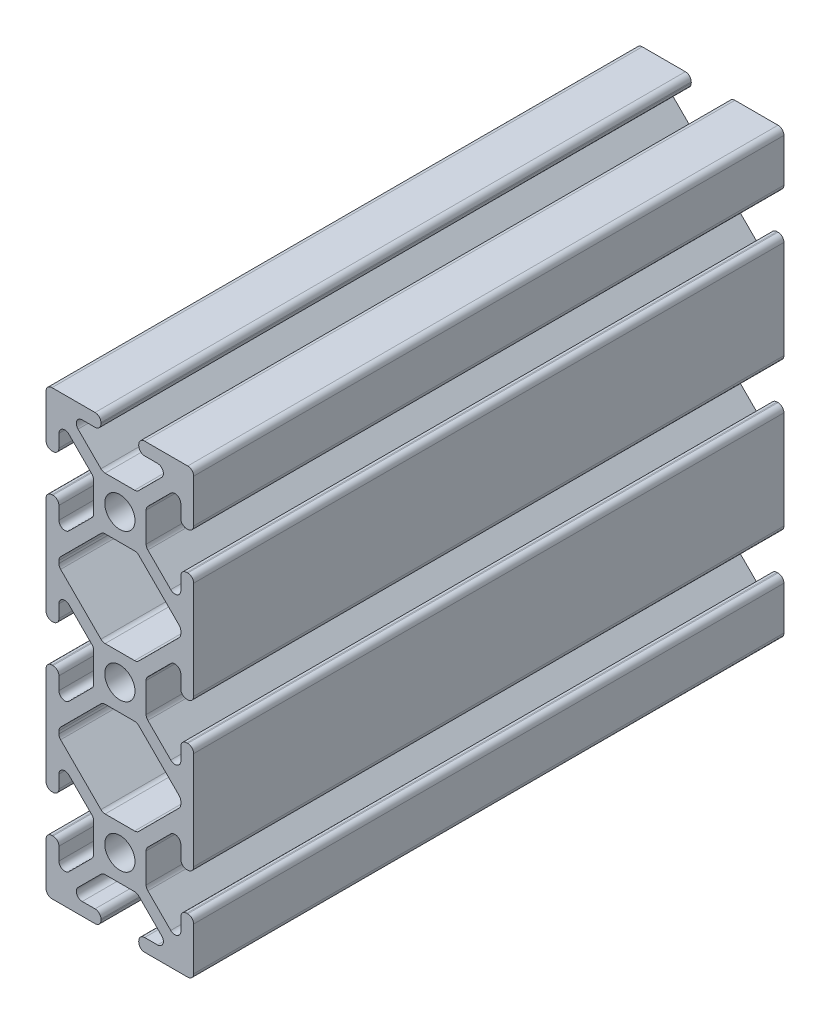
SolidWorks part; units mm, degrees
ref_plane "Front Plane" through (0, 0, 0) normal (0, 0, 1) x (1, 0, 0)
ref_plane "Top Plane" through (0, 0, 0) normal (0, 1, 0) x (1, 0, 0)
ref_plane "Right Plane" through (0, 0, 0) normal (1, 0, 0) x (0, 0, -1)
sketch "Sketch1" plane through (0, 0, 0) normal (0, 0, 1) x (1, 0, 0)
  line L0 (-12.7, 38.1) -> (-12.7, 12.7) construction
  line L1 (-12.7, -38.1) -> (12.7, -38.1) construction
  line L2 (-12.7, 12.7) -> (-12.7, -12.7) construction
  line L3 (-12.7, 38.1) -> (12.7, 38.1) construction
  line L4 (-12.7, -12.7) -> (-12.7, -38.1) construction
  line L5 (-12.7, -38.1) -> (12.7, 38.1) construction
  line L6 (-12.7, 38.1) -> (12.7, -38.1) construction
  line L7 (12.7, 38.1) -> (12.7, 12.7) construction
  line L8 (12.7, 12.7) -> (12.7, -12.7) construction
  line L9 (12.7, -12.7) -> (12.7, -38.1) construction
  line L10 (-12.7, 12.7) -> (12.7, 12.7) construction
  line L11 (-12.7, -12.7) -> (12.7, -12.7) construction
  line L12 (12.7, -12.7) -> (-12.7, -38.1) construction
  line L13 (12.7, -38.1) -> (-12.7, -12.7) construction
  line L14 (0, 38.1) -> (0, -38.1) construction
  line L15 (12.7, 12.7) -> (-12.7, 38.1) construction
  line L16 (12.7, 38.1) -> (-12.7, 12.7) construction
  line L17 (-12.7, 37.084) -> (-12.7, 29.6672)
  line L18 (-11.684, 28.6512) -> (-11.5062, 28.6512)
  line L19 (-10.4902, 29.6672) -> (-10.4902, 31.8748)
  line L20 (-8.7558, 32.5932) -> (-4.8188, 28.6562)
  line L21 (-4.5212, 27.9378) -> (-4.5212, 22.8622)
  line L22 (-4.8188, 22.1438) -> (-8.7558, 18.2068)
  line L23 (-10.4902, 18.9252) -> (-10.4902, 21.1328)
  line L24 (-11.5062, 22.1488) -> (-11.684, 22.1488)
  line L25 (-12.7, 21.1328) -> (-12.7, 4.2672)
  line L26 (-12.7, 0) -> (12.7, 0) construction
  line L27 (-12.7, -25.4) -> (12.7, -25.4) construction
  line L28 (-12.7, 25.4) -> (12.7, 25.4) construction
  line L29 (4.2672, 38.1) -> (11.684, 38.1)
  line L30 (3.2512, 36.9062) -> (3.2512, 37.084)
  line L31 (6.4748, 35.8902) -> (4.2672, 35.8902)
  line L32 (3.2562, 30.2188) -> (7.1932, 34.1558)
  line L33 (-2.5378, 29.9212) -> (2.5378, 29.9212)
  line L34 (-7.1932, 34.1558) -> (-3.2562, 30.2188)
  line L35 (-4.2672, 35.8902) -> (-6.4748, 35.8902)
  line L36 (-3.2512, 37.084) -> (-3.2512, 36.9062)
  line L37 (-11.684, 38.1) -> (-4.2672, 38.1)
  line L38 (4.5212, 2.5378) -> (4.5212, -2.5378)
  line L39 (11.5062, 22.1488) -> (11.684, 22.1488)
  line L40 (10.4902, 18.9252) -> (10.4902, 21.1328)
  line L41 (4.8188, 22.1438) -> (8.7558, 18.2068)
  line L42 (4.5212, 27.9378) -> (4.5212, 22.8622)
  line L43 (8.7558, 32.5932) -> (4.8188, 28.6562)
  line L44 (10.4902, 29.6672) -> (10.4902, 31.8748)
  line L45 (11.684, 28.6512) -> (11.5062, 28.6512)
  line L46 (12.7, 37.084) -> (12.7, 29.6672)
  line L47 (-10.4902, 12.4736) -> (-10.4902, 12.9264)
  line L48 (-10.1926, 13.6448) -> (-3.2562, 20.5812)
  line L49 (-2.5378, 20.8788) -> (2.5378, 20.8788)
  line L50 (10.4902, 12.4736) -> (10.4902, 12.9264)
  line L51 (10.1926, 13.6448) -> (3.2562, 20.5812)
  line L52 (10.1926, 11.7552) -> (3.2562, 4.8188)
  line L53 (-2.5378, 4.5212) -> (2.5378, 4.5212)
  line L54 (-10.1926, 11.7552) -> (-3.2562, 4.8188)
  line L55 (-2.5378, -4.5212) -> (2.5378, -4.5212)
  line L56 (-10.1926, -11.7552) -> (-3.2562, -4.8188)
  line L57 (10.1926, -11.7552) -> (3.2562, -4.8188)
  line L58 (10.4902, -12.4736) -> (10.4902, -12.9264)
  line L59 (10.1926, -13.6448) -> (3.2562, -20.5812)
  line L60 (-2.5378, -20.8788) -> (2.5378, -20.8788)
  line L61 (-10.1926, -13.6448) -> (-3.2562, -20.5812)
  line L62 (-10.4902, -12.4736) -> (-10.4902, -12.9264)
  line L63 (4.8188, -3.2562) -> (8.7558, -7.1932)
  line L64 (11.5062, -22.1488) -> (11.684, -22.1488)
  line L65 (10.4902, -18.9252) -> (10.4902, -21.1328)
  line L66 (4.8188, -22.1438) -> (8.7558, -18.2068)
  line L67 (4.5212, -27.9378) -> (4.5212, -22.8622)
  line L68 (8.7558, -32.5932) -> (4.8188, -28.6562)
  line L69 (10.4902, -29.6672) -> (10.4902, -31.8748)
  line L70 (11.684, -28.6512) -> (11.5062, -28.6512)
  line L71 (12.7, -37.084) -> (12.7, -29.6672)
  line L72 (3.2512, -36.9062) -> (3.2512, -37.084)
  line L73 (6.4748, -35.8902) -> (4.2672, -35.8902)
  line L74 (3.2562, -30.2188) -> (7.1932, -34.1558)
  line L75 (-2.5378, -29.9212) -> (2.5378, -29.9212)
  line L76 (-7.1932, -34.1558) -> (-3.2562, -30.2188)
  line L77 (-4.2672, -35.8902) -> (-6.4748, -35.8902)
  line L78 (-3.2512, -37.084) -> (-3.2512, -36.9062)
  line L79 (-11.684, -38.1) -> (-4.2672, -38.1)
  line L80 (4.2672, -38.1) -> (11.684, -38.1)
  line L81 (4.8188, 3.2562) -> (8.7558, 7.1932)
  line L82 (-11.5062, -22.1488) -> (-11.684, -22.1488)
  line L83 (-10.4902, -18.9252) -> (-10.4902, -21.1328)
  line L84 (-4.8188, -22.1438) -> (-8.7558, -18.2068)
  line L85 (-4.5212, -27.9378) -> (-4.5212, -22.8622)
  line L86 (-8.7558, -32.5932) -> (-4.8188, -28.6562)
  line L87 (-10.4902, -29.6672) -> (-10.4902, -31.8748)
  line L88 (-11.684, -28.6512) -> (-11.5062, -28.6512)
  line L89 (-12.7, -37.084) -> (-12.7, -29.6672)
  line L90 (-4.8188, 3.2562) -> (-8.7558, 7.1932)
  line L91 (-10.4902, 6.4748) -> (-10.4902, 4.2672)
  line L92 (-11.5062, 3.2512) -> (-11.684, 3.2512)
  line L93 (-4.5212, 2.5378) -> (-4.5212, -2.5378)
  line L94 (-12.7, -21.1328) -> (-12.7, -4.2672)
  line L95 (-4.8188, -3.2562) -> (-8.7558, -7.1932)
  line L96 (-10.4902, -6.4748) -> (-10.4902, -4.2672)
  line L97 (-11.5062, -3.2512) -> (-11.684, -3.2512)
  line L98 (10.4902, -6.4748) -> (10.4902, -4.2672)
  line L99 (10.4902, 6.4748) -> (10.4902, 4.2672)
  line L100 (11.5062, 3.2512) -> (11.684, 3.2512)
  line L101 (11.5062, -3.2512) -> (11.684, -3.2512)
  line L102 (12.7, -21.1328) -> (12.7, -4.2672)
  line L103 (12.7, 21.1328) -> (12.7, 4.2672)
  circle A0 centre (0, 25.4) radius 2.6035
  circle A1 centre (0, 0) radius 2.6035
  circle A2 centre (0, -25.4) radius 2.6035
  arc A3 (-12.7, 21.1328) -> (-11.684, 22.1488) centre (-11.684, 21.1328) cw
  arc A4 (-11.5062, 22.1488) -> (-10.4902, 21.1328) centre (-11.5062, 21.1328) cw
  arc A5 (-10.4902, 18.9252) -> (-8.7558, 18.2068) centre (-9.4742, 18.9252) ccw
  arc A6 (-4.8188, 22.1438) -> (-4.5212, 22.8622) centre (-5.5372, 22.8622) ccw
  arc A7 (-4.5212, 27.9378) -> (-4.8188, 28.6562) centre (-5.5372, 27.9378) ccw
  arc A8 (-8.7558, 32.5932) -> (-10.4902, 31.8748) centre (-9.4742, 31.8748) ccw
  arc A9 (-10.4902, 29.6672) -> (-11.5062, 28.6512) centre (-11.5062, 29.6672) cw
  arc A10 (-11.684, 28.6512) -> (-12.7, 29.6672) centre (-11.684, 29.6672) cw
  arc A11 (4.2672, 38.1) -> (3.2512, 37.084) centre (4.2672, 37.084) ccw
  arc A12 (3.2512, 36.9062) -> (4.2672, 35.8902) centre (4.2672, 36.9062) ccw
  arc A13 (6.4748, 35.8902) -> (7.1932, 34.1558) centre (6.4748, 34.8742) cw
  arc A14 (3.2562, 30.2188) -> (2.5378, 29.9212) centre (2.5378, 30.9372) cw
  arc A15 (-2.5378, 29.9212) -> (-3.2562, 30.2188) centre (-2.5378, 30.9372) cw
  arc A16 (-7.1932, 34.1558) -> (-6.4748, 35.8902) centre (-6.4748, 34.8742) cw
  arc A17 (-4.2672, 35.8902) -> (-3.2512, 36.9062) centre (-4.2672, 36.9062) ccw
  arc A18 (-3.2512, 37.084) -> (-4.2672, 38.1) centre (-4.2672, 37.084) ccw
  arc A19 (12.7, 21.1328) -> (11.684, 22.1488) centre (11.684, 21.1328) ccw
  arc A20 (11.5062, 22.1488) -> (10.4902, 21.1328) centre (11.5062, 21.1328) ccw
  arc A21 (10.4902, 18.9252) -> (8.7558, 18.2068) centre (9.4742, 18.9252) cw
  arc A22 (4.8188, 22.1438) -> (4.5212, 22.8622) centre (5.5372, 22.8622) cw
  arc A23 (4.5212, 27.9378) -> (4.8188, 28.6562) centre (5.5372, 27.9378) cw
  arc A24 (8.7558, 32.5932) -> (10.4902, 31.8748) centre (9.4742, 31.8748) cw
  arc A25 (10.4902, 29.6672) -> (11.5062, 28.6512) centre (11.5062, 29.6672) ccw
  arc A26 (11.684, 28.6512) -> (12.7, 29.6672) centre (11.684, 29.6672) ccw
  arc A27 (12.7, 37.084) -> (11.684, 38.1) centre (11.684, 37.084) ccw
  arc A28 (-11.684, 38.1) -> (-12.7, 37.084) centre (-11.684, 37.084) ccw
  arc A29 (-10.1926, 13.6448) -> (-10.4902, 12.9264) centre (-9.4742, 12.9264) ccw
  arc A30 (-2.5378, 20.8788) -> (-3.2562, 20.5812) centre (-2.5378, 19.8628) ccw
  arc A31 (10.1926, 13.6448) -> (10.4902, 12.9264) centre (9.4742, 12.9264) cw
  arc A32 (2.5378, 20.8788) -> (3.2562, 20.5812) centre (2.5378, 19.8628) cw
  arc A33 (10.1926, 11.7552) -> (10.4902, 12.4736) centre (9.4742, 12.4736) ccw
  arc A34 (2.5378, 4.5212) -> (3.2562, 4.8188) centre (2.5378, 5.5372) ccw
  arc A35 (-2.5378, 4.5212) -> (-3.2562, 4.8188) centre (-2.5378, 5.5372) cw
  arc A36 (-10.1926, 11.7552) -> (-10.4902, 12.4736) centre (-9.4742, 12.4736) cw
  arc A37 (2.5378, -4.5212) -> (3.2562, -4.8188) centre (2.5378, -5.5372) cw
  arc A38 (-2.5378, -4.5212) -> (-3.2562, -4.8188) centre (-2.5378, -5.5372) ccw
  arc A39 (10.1926, -11.7552) -> (10.4902, -12.4736) centre (9.4742, -12.4736) cw
  arc A40 (10.1926, -13.6448) -> (10.4902, -12.9264) centre (9.4742, -12.9264) ccw
  arc A41 (2.5378, -20.8788) -> (3.2562, -20.5812) centre (2.5378, -19.8628) ccw
  arc A42 (-2.5378, -20.8788) -> (-3.2562, -20.5812) centre (-2.5378, -19.8628) cw
  arc A43 (-10.1926, -13.6448) -> (-10.4902, -12.9264) centre (-9.4742, -12.9264) cw
  arc A44 (-10.1926, -11.7552) -> (-10.4902, -12.4736) centre (-9.4742, -12.4736) ccw
  arc A45 (12.7, -21.1328) -> (11.684, -22.1488) centre (11.684, -21.1328) cw
  arc A46 (11.5062, -22.1488) -> (10.4902, -21.1328) centre (11.5062, -21.1328) cw
  arc A47 (10.4902, -18.9252) -> (8.7558, -18.2068) centre (9.4742, -18.9252) ccw
  arc A48 (4.8188, -22.1438) -> (4.5212, -22.8622) centre (5.5372, -22.8622) ccw
  arc A49 (4.5212, -27.9378) -> (4.8188, -28.6562) centre (5.5372, -27.9378) ccw
  arc A50 (8.7558, -32.5932) -> (10.4902, -31.8748) centre (9.4742, -31.8748) ccw
  arc A51 (10.4902, -29.6672) -> (11.5062, -28.6512) centre (11.5062, -29.6672) cw
  arc A52 (11.684, -28.6512) -> (12.7, -29.6672) centre (11.684, -29.6672) cw
  arc A53 (4.2672, -38.1) -> (3.2512, -37.084) centre (4.2672, -37.084) cw
  arc A54 (3.2512, -36.9062) -> (4.2672, -35.8902) centre (4.2672, -36.9062) cw
  arc A55 (6.4748, -35.8902) -> (7.1932, -34.1558) centre (6.4748, -34.8742) ccw
  arc A56 (3.2562, -30.2188) -> (2.5378, -29.9212) centre (2.5378, -30.9372) ccw
  arc A57 (-2.5378, -29.9212) -> (-3.2562, -30.2188) centre (-2.5378, -30.9372) ccw
  arc A58 (-7.1932, -34.1558) -> (-6.4748, -35.8902) centre (-6.4748, -34.8742) ccw
  arc A59 (-4.2672, -35.8902) -> (-3.2512, -36.9062) centre (-4.2672, -36.9062) cw
  arc A60 (-3.2512, -37.084) -> (-4.2672, -38.1) centre (-4.2672, -37.084) cw
  arc A61 (12.7, -37.084) -> (11.684, -38.1) centre (11.684, -37.084) cw
  arc A62 (-12.7, -21.1328) -> (-11.684, -22.1488) centre (-11.684, -21.1328) ccw
  arc A63 (-11.5062, -22.1488) -> (-10.4902, -21.1328) centre (-11.5062, -21.1328) ccw
  arc A64 (-10.4902, -18.9252) -> (-8.7558, -18.2068) centre (-9.4742, -18.9252) cw
  arc A65 (-4.8188, -22.1438) -> (-4.5212, -22.8622) centre (-5.5372, -22.8622) cw
  arc A66 (-4.5212, -27.9378) -> (-4.8188, -28.6562) centre (-5.5372, -27.9378) cw
  arc A67 (-8.7558, -32.5932) -> (-10.4902, -31.8748) centre (-9.4742, -31.8748) cw
  arc A68 (-10.4902, -29.6672) -> (-11.5062, -28.6512) centre (-11.5062, -29.6672) ccw
  arc A69 (-11.684, -28.6512) -> (-12.7, -29.6672) centre (-11.684, -29.6672) ccw
  arc A70 (-11.684, -38.1) -> (-12.7, -37.084) centre (-11.684, -37.084) cw
  arc A71 (-4.8188, 3.2562) -> (-4.5212, 2.5378) centre (-5.5372, 2.5378) cw
  arc A72 (-10.4902, 6.4748) -> (-8.7558, 7.1932) centre (-9.4742, 6.4748) cw
  arc A73 (-11.5062, 3.2512) -> (-10.4902, 4.2672) centre (-11.5062, 4.2672) ccw
  arc A74 (-12.7, 4.2672) -> (-11.684, 3.2512) centre (-11.684, 4.2672) ccw
  arc A75 (-4.8188, -3.2562) -> (-4.5212, -2.5378) centre (-5.5372, -2.5378) ccw
  arc A76 (-10.4902, -6.4748) -> (-8.7558, -7.1932) centre (-9.4742, -6.4748) ccw
  arc A77 (-11.5062, -3.2512) -> (-10.4902, -4.2672) centre (-11.5062, -4.2672) cw
  arc A78 (-12.7, -4.2672) -> (-11.684, -3.2512) centre (-11.684, -4.2672) cw
  arc A79 (4.8188, 3.2562) -> (4.5212, 2.5378) centre (5.5372, 2.5378) ccw
  arc A80 (4.8188, -3.2562) -> (4.5212, -2.5378) centre (5.5372, -2.5378) cw
  arc A81 (10.4902, 6.4748) -> (8.7558, 7.1932) centre (9.4742, 6.4748) ccw
  arc A82 (10.4902, -6.4748) -> (8.7558, -7.1932) centre (9.4742, -6.4748) cw
  arc A83 (11.5062, -3.2512) -> (10.4902, -4.2672) centre (11.5062, -4.2672) ccw
  arc A84 (11.5062, 3.2512) -> (10.4902, 4.2672) centre (11.5062, 4.2672) cw
  arc A85 (12.7, -4.2672) -> (11.684, -3.2512) centre (11.684, -4.2672) ccw
  arc A86 (12.7, 4.2672) -> (11.684, 3.2512) centre (11.684, 4.2672) cw
  point P0 (0, 0)
  point P26 (-12.7, 22.1488)
  point P41 (-12.7, 28.6512)
  point P107 (-6.7244, 17.113)
  point P120 (0, 20.8788)
  point P121 (10.4902, 12.7)
  point P132 (-10.4902, 12.7)
  point P249 (-4.5212, 0)
  dimension "D2" = 5.207
  dimension "D8" = 1.016
  dimension "D9" = 3.2512
  dimension "D10" = 1.1049
  dimension "D1" = 25.4
  dimension "D3" = 2.2098
  dimension "D4" = 6.5024
  dimension "D5" = 4.5212
  dimension "D6" = 1.1049
  dimension "D7" = 1.1049
  dimension "D11" = 4.5212
extrude "Main Extrusion" add sketch "Sketch1" along normal mid plane 101.6
sketch "Sketch2" plane through (0, 0, 50.8) normal (0, 0, 1) x (1, 0, 0)
  line L0 (-4.2672, 38.1) -> (-11.684, 38.1) construction
  line L1 (-12.7, -38.1) -> (12.7, -38.1) construction
  line L2 (-12.7, 38.1) -> (-12.7, 12.7) construction
  line L3 (-12.7, 38.1) -> (12.7, 38.1) construction
  line L4 (-12.7, 21.1328) -> (-12.7, 4.2672) construction
  line L5 (-12.7, -38.1) -> (12.7, 38.1) construction
  line L6 (-12.7, 38.1) -> (12.7, -38.1) construction
  line L7 (-12.7, 12.7) -> (-12.7, -12.7) construction
  line L8 (0, 38.1) -> (0, -38.1) construction
  line L9 (-12.7, -4.2672) -> (-12.7, -21.1328) construction
  line L10 (-12.7, -12.7) -> (-12.7, -38.1) construction
  line L11 (12.7, 38.1) -> (12.7, 12.7) construction
  line L12 (12.7, 4.2672) -> (12.7, 21.1328) construction
  line L13 (12.7, 12.7) -> (12.7, -12.7) construction
  line L14 (12.7, -21.1328) -> (12.7, -4.2672) construction
  line L15 (12.7, -12.7) -> (12.7, -38.1) construction
  line L16 (-12.7, 25.4) -> (12.7, 25.4) construction
  line L17 (-12.7, 0) -> (12.7, 0) construction
  line L18 (-12.7, -25.4) -> (12.7, -25.4) construction
  line L19 (-12.7, 12.7) -> (12.7, 12.7) construction
  line L20 (-12.7, -12.7) -> (12.7, -12.7) construction
  line L21 (-3.2512, 36.9062) -> (-3.2512, 37.084) construction
  line L22 (-10.4902, 38.1) -> (-9.4742, 38.1)
  line L23 (-6.477, 38.1) -> (-5.461, 38.1)
  line L24 (-12.7, 38.1) -> (12.7, 12.7) construction
  line L25 (12.7, 12.7) -> (-12.7, -12.7) construction
  line L26 (-12.7, -12.7) -> (12.7, -38.1) construction
  line L27 (-12.7, -38.1) -> (12.7, -12.7) construction
  line L28 (12.7, -12.7) -> (-12.7, 12.7) construction
  line L29 (-12.7, 12.7) -> (12.7, 38.1) construction
  line L30 (6.477, 38.1) -> (5.461, 38.1)
  line L31 (10.4902, 38.1) -> (9.4742, 38.1)
  line L32 (-12.7, 14.9098) -> (-12.7, 15.9258)
  line L33 (-12.7, 18.923) -> (-12.7, 19.939)
  line L34 (-12.7, 31.877) -> (-12.7, 30.861)
  line L35 (-12.7, 35.8902) -> (-12.7, 34.8742)
  line L36 (12.7, 35.8902) -> (12.7, 34.8742)
  line L37 (12.7, 31.877) -> (12.7, 30.861)
  line L38 (12.7, 18.923) -> (12.7, 19.939)
  line L39 (12.7, 14.9098) -> (12.7, 15.9258)
  line L40 (12.7, 10.4902) -> (12.7, 9.4742)
  line L41 (12.7, 6.477) -> (12.7, 5.461)
  line L42 (-12.7, 10.4902) -> (-12.7, 9.4742)
  line L43 (-12.7, 6.477) -> (-12.7, 5.461)
  line L44 (12.7, -6.477) -> (12.7, -5.461)
  line L45 (12.7, -10.4902) -> (12.7, -9.4742)
  line L46 (12.7, -14.9098) -> (12.7, -15.9258)
  line L47 (12.7, -18.923) -> (12.7, -19.939)
  line L48 (12.7, -31.877) -> (12.7, -30.861)
  line L49 (12.7, -35.8902) -> (12.7, -34.8742)
  line L50 (10.4902, -38.1) -> (9.4742, -38.1)
  line L51 (6.477, -38.1) -> (5.461, -38.1)
  line L52 (-6.477, -38.1) -> (-5.461, -38.1)
  line L53 (-10.4902, -38.1) -> (-9.4742, -38.1)
  line L54 (-12.7, -35.8902) -> (-12.7, -34.8742)
  line L55 (-12.7, -31.877) -> (-12.7, -30.861)
  line L56 (-12.7, -18.923) -> (-12.7, -19.939)
  line L57 (-12.7, -14.9098) -> (-12.7, -15.9258)
  line L58 (-12.7, -10.4902) -> (-12.7, -9.4742)
  line L59 (-12.7, -6.477) -> (-12.7, -5.461)
  arc A0 (-10.4902, 38.1) -> (-9.4742, 38.1) centre (-9.9822, 38.1) ccw
  arc A1 (-6.477, 38.1) -> (-5.461, 38.1) centre (-5.969, 38.1) ccw
  arc A2 (6.477, 38.1) -> (5.461, 38.1) centre (5.969, 38.1) cw
  arc A3 (10.4902, 38.1) -> (9.4742, 38.1) centre (9.9822, 38.1) cw
  arc A4 (-12.7, 14.9098) -> (-12.7, 15.9258) centre (-12.7, 15.4178) ccw
  arc A5 (-12.7, 18.923) -> (-12.7, 19.939) centre (-12.7, 19.431) ccw
  arc A6 (-12.7, 31.877) -> (-12.7, 30.861) centre (-12.7, 31.369) cw
  arc A7 (-12.7, 35.8902) -> (-12.7, 34.8742) centre (-12.7, 35.3822) cw
  arc A8 (12.7, 35.8902) -> (12.7, 34.8742) centre (12.7, 35.3822) ccw
  arc A9 (12.7, 31.877) -> (12.7, 30.861) centre (12.7, 31.369) ccw
  arc A10 (12.7, 18.923) -> (12.7, 19.939) centre (12.7, 19.431) cw
  arc A11 (12.7, 14.9098) -> (12.7, 15.9258) centre (12.7, 15.4178) cw
  arc A12 (12.7, 10.4902) -> (12.7, 9.4742) centre (12.7, 9.9822) ccw
  arc A13 (12.7, 6.477) -> (12.7, 5.461) centre (12.7, 5.969) ccw
  arc A14 (-12.7, 10.4902) -> (-12.7, 9.4742) centre (-12.7, 9.9822) cw
  arc A15 (-12.7, 6.477) -> (-12.7, 5.461) centre (-12.7, 5.969) cw
  arc A16 (12.7, -6.477) -> (12.7, -5.461) centre (12.7, -5.969) cw
  arc A17 (12.7, -10.4902) -> (12.7, -9.4742) centre (12.7, -9.9822) cw
  arc A18 (12.7, -14.9098) -> (12.7, -15.9258) centre (12.7, -15.4178) ccw
  arc A19 (12.7, -18.923) -> (12.7, -19.939) centre (12.7, -19.431) ccw
  arc A20 (12.7, -31.877) -> (12.7, -30.861) centre (12.7, -31.369) cw
  arc A21 (12.7, -35.8902) -> (12.7, -34.8742) centre (12.7, -35.3822) cw
  arc A22 (10.4902, -38.1) -> (9.4742, -38.1) centre (9.9822, -38.1) ccw
  arc A23 (6.477, -38.1) -> (5.461, -38.1) centre (5.969, -38.1) ccw
  arc A24 (-6.477, -38.1) -> (-5.461, -38.1) centre (-5.969, -38.1) cw
  arc A25 (-10.4902, -38.1) -> (-9.4742, -38.1) centre (-9.9822, -38.1) cw
  arc A26 (-12.7, -35.8902) -> (-12.7, -34.8742) centre (-12.7, -35.3822) ccw
  arc A27 (-12.7, -31.877) -> (-12.7, -30.861) centre (-12.7, -31.369) ccw
  arc A28 (-12.7, -18.923) -> (-12.7, -19.939) centre (-12.7, -19.431) cw
  arc A29 (-12.7, -14.9098) -> (-12.7, -15.9258) centre (-12.7, -15.4178) cw
  arc A30 (-12.7, -10.4902) -> (-12.7, -9.4742) centre (-12.7, -9.9822) ccw
  arc A31 (-12.7, -6.477) -> (-12.7, -5.461) centre (-12.7, -5.969) ccw
  point P0 (0, 0)
  dimension "D1" = 0.508
  dimension "D2" = 2.2098
  dimension "D3" = 2.2098
